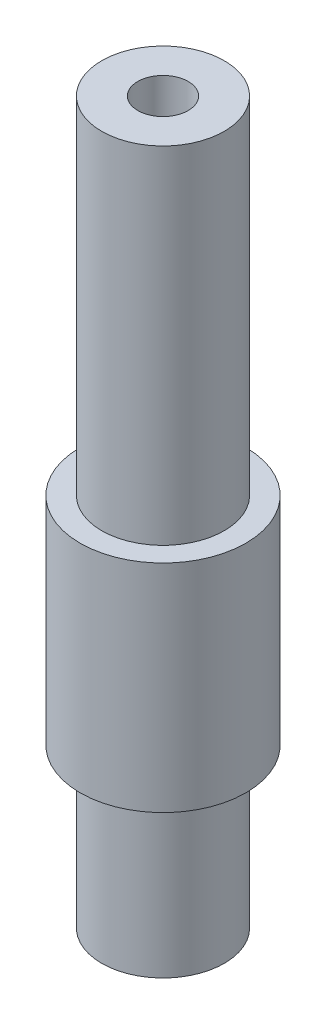
SolidWorks part; units mm, degrees
ref_plane "前视基准面" through (0, 0, 0) normal (0, 0, 1) x (1, 0, 0)
ref_plane "上视基准面" through (0, 0, 0) normal (0, 1, 0) x (1, 0, 0)
ref_plane "右视基准面" through (0, 0, 0) normal (1, 0, 0) x (0, 0, -1)
sketch "草图1" plane through (0, 0, 0) normal (0, 1, 0) x (1, 0, 0)
  circle A0 centre (0, 0) radius 8.5
  dimension "D1" = 17
extrude "凸台-拉伸1" add sketch "草图1" along normal blind 22
sketch "草图2" plane through (0, 22, 0) normal (0, 1, 0) x (1, 0, 0)
  circle A0 centre (0, 0) radius 11.5
  dimension "D1" = 23
extrude "凸台-拉伸2" add sketch "草图2" along normal blind 30
sketch "草图3" plane through (0, 52, 0) normal (0, 1, 0) x (1, 0, 0)
  circle A0 centre (0, 0) radius 8.5
  dimension "D1" = 17
extrude "凸台-拉伸3" add sketch "草图3" along normal blind 48
sketch "草图4" plane through (0, 0, 0) normal (1, 0, 0) x (0, 0, -1)
  line L0 (0, 17.5) -> (0, 4.5) construction
  line L1 (0, 12.65) -> (0, -12.65) construction
  line L2 (2.5, 17.5) -> (2.5, 4.5)
  line L3 (-2.5, 17.5) -> (-2.5, 4.5)
  arc A0 (2.5, 17.5) -> (-2.5, 17.5) centre (0, 17.5) ccw
  arc A1 (-2.5, 4.5) -> (2.5, 4.5) centre (0, 4.5) ccw
  point P5 (0, 11)
  dimension "D1" = 18
  dimension "D3" = 2
  dimension "D2" = 5
extrude "切除-拉伸1" cut sketch "草图4" against normal blind 48 from offset 5.5 offset against normal yes
sketch "草图5" plane through (0, 0, 0) normal (1, 0, 0) x (0, 0, -1)
  line L0 (0, 96) -> (0, 87.1336) construction
  line L1 (0, 12.65) -> (0, -12.65) construction
  line L2 (2.5, 96) -> (2.5, 87.1336)
  line L3 (-2.5, 96) -> (-2.5, 87.1336)
  line L6 (8.5, 100) -> (-8.5, 100) construction
  arc A0 (2.5, 96) -> (-2.5, 96) centre (0, 96) ccw
  arc A1 (-2.5, 87.1336) -> (2.5, 87.1336) centre (0, 87.1336) ccw
  point P5 (0, 91.5668)
  dimension "D2" = 1.5
  dimension "D1" = 5
extrude "切除-拉伸2" cut sketch "草图5" against normal blind 5.5 from offset 5.5 offset against normal yes
hole_wizard "M8x1.0 螺纹孔1" positions "草图6" profile "草图7" tap size "M8x1.0" standard "GB"
sketch "草图6" plane through (0, 100, 0) normal (0, 1, 0) x (1, 0, 0)
  point P0 (0, 0)
sketch "草图7" plane through (0, 100, 0) normal (1, 0, 0) x (0, 0, 1)
  line L0 (0, 0) -> (0, 20.103)
  line L1 (0, 20.103) -> (3.5, 18)
  line L2 (3.5, 18) -> (3.5, 0)
  line L5 (3.5, 0) -> (0, 0)
  line L10 (0, 20.103) -> (-3.5, 18) construction
  line L11 (0, -6.35) -> (0, 107.95) construction
  dimension "螺纹孔钻头直径" = 7
  dimension "螺纹孔钻头深度" = 18
  dimension "导头角度" = 118
cosmetic thread "孔螺纹线1" parameters "D1"=15, "D2"=8
